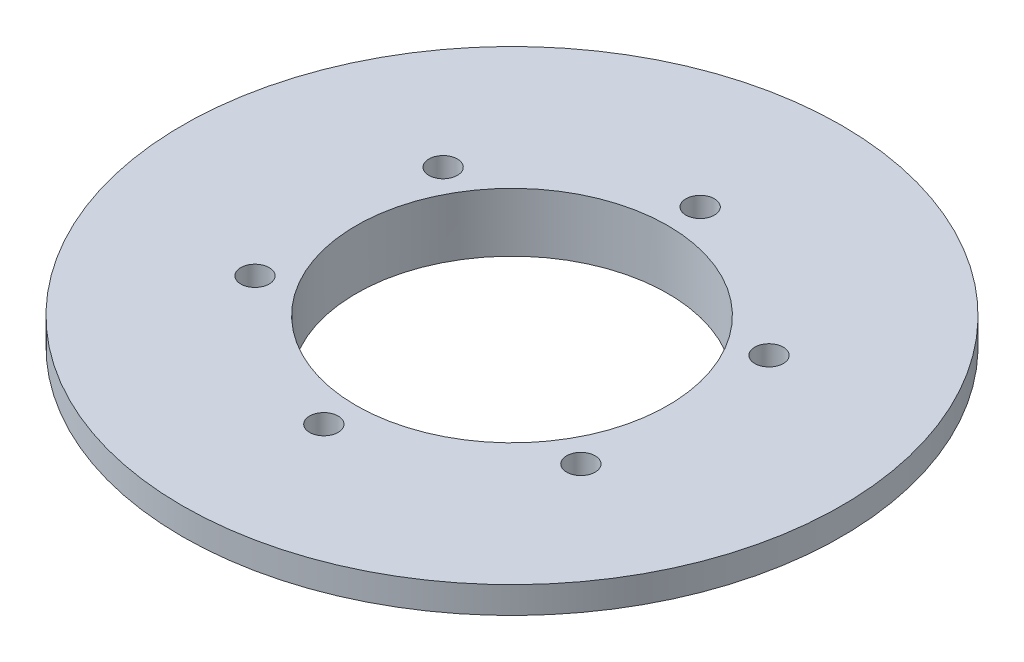
SolidWorks part; units mm, degrees
ref_plane "Front Plane" through (0, 0, 0) normal (0, 0, 1) x (1, 0, 0)
ref_plane "Top Plane" through (0, 0, 0) normal (0, 1, 0) x (1, 0, 0)
ref_plane "Right Plane" through (0, 0, 0) normal (1, 0, 0) x (0, 0, -1)
sketch "Sketch2" plane through (0, 0, 0) normal (0, 0, 1) x (1, 0, 0)
  line L0 (-34.3228, 0) -> (-37, 0)
  line L1 (0, 0) -> (-29.6772, 0)
  line L2 (0, 0) -> (0, 3)
  line L3 (0, 3) -> (-37, 3)
  line L4 (-37, 0) -> (-37, 3)
  arc A0 (-29.6772, 0) -> (-34.3228, 0) centre (-32, -0.1) ccw
  dimension "D3" = 4.65
  dimension "D1" = 37
  dimension "D2" = 3
  dimension "D4" = 0.1
  dimension "D5" = 32
revolve "Revolve1" add sketch "Sketch2" angle 360 about L2
sketch "Sketch3" plane through (0, 0, 0) normal (0, -1, 0) x (1, 0, 0)
  circle A0 centre (0, 0) radius 24.75
  dimension "D1" = 49.5
extrude "Boss-Extrude1" add sketch "Sketch3" along normal blind 3.6
sketch "Sketch4" plane through (0, 3, 0) normal (0, 1, 0) x (1, 0, 0)
  circle A0 centre (0, 0) radius 17.5
  dimension "D1" = 35
extrude "Cut-Extrude1" cut sketch "Sketch4" against normal through all both and the other way through all
sketch "Sketch5" plane through (0, -3.6, 0) normal (0, -1, 0) x (1, 0, 0)
  line L0 (-17.5, 0) -> (-24.75, 0)
  circle A0 centre (0, 0) radius 21.125 construction
  circle A4 centre (0, 0) radius 17.5 construction
  circle A5 centre (0, 0) radius 24.75 construction
  circle A6 centre (0, 21.125) radius 1.6
  circle A7 centre (18.2948, 10.5625) radius 1.6
  circle A8 centre (18.2948, -10.5625) radius 1.6
  circle A9 centre (0, -21.125) radius 1.6
  circle A10 centre (-18.2948, -10.5625) radius 1.6
  circle A11 centre (-18.2948, 10.5625) radius 1.6
  point P10 (-21.125, 0)
  point P26 (0, 0)
  dimension "D1" = 3.2
  dimension "D2" = 6
extrude "Cut-Extrude2" cut sketch "Sketch5" against normal through all both and the other way through all contours A11 | A10 | A9 | A6 | A8 | A7
